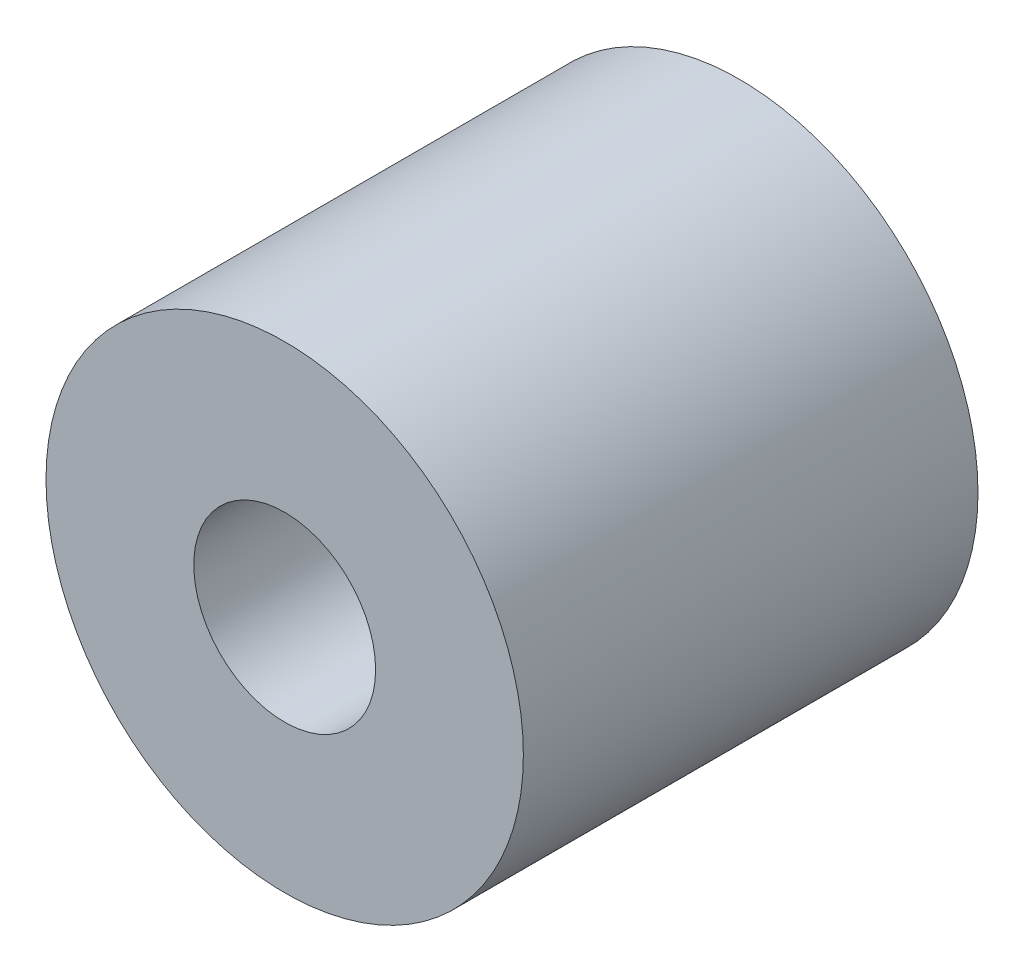
SolidWorks part; units mm, degrees
ref_plane "Спереди" through (0, 0, 0) normal (0, 0, 1) x (1, 0, 0)
ref_plane "Сверху" through (0, 0, 0) normal (0, 1, 0) x (1, 0, 0)
ref_plane "Справа" through (0, 0, 0) normal (1, 0, 0) x (0, 0, -1)
sketch "Эскиз1" plane through (0, 0, 0) normal (0, 0, 1) x (1, 0, 0)
  circle A0 centre (0, 0) radius 10.5
  dimension "D1" = 21
extrude "Бобышка-Вытянуть1" add sketch "Эскиз1" along normal blind 20 contours A0
sketch "Эскиз2" plane through (0, 0, 20) normal (0, 0, 1) x (1, 0, 0)
  circle A0 centre (0, 0) radius 4
  dimension "D1" = 8
extrude "Вырез-Вытянуть1" cut sketch "Эскиз2" against normal blind 20
